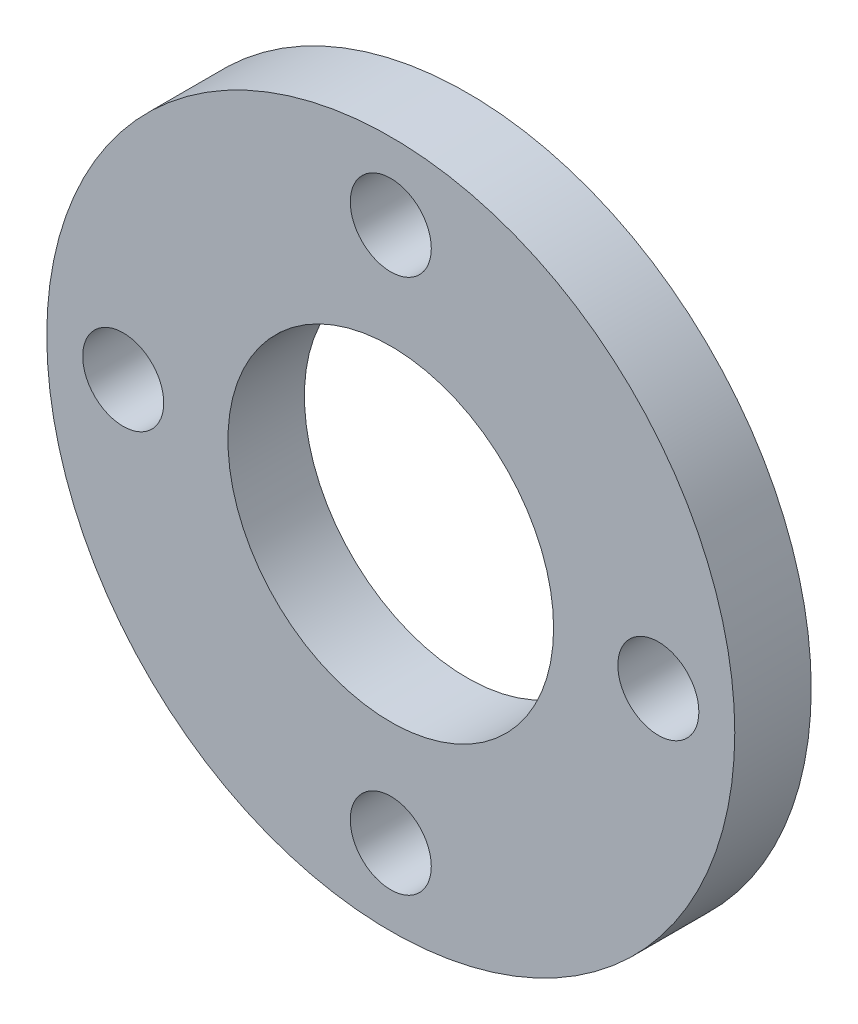
SolidWorks part; units mm, degrees
ref_plane "Płaszczyzna przednia" through (0, 0, 0) normal (0, 0, 1) x (1, 0, 0)
ref_plane "Płaszczyzna górna" through (0, 0, 0) normal (0, 1, 0) x (1, 0, 0)
ref_plane "Płaszczyzna prawa" through (0, 0, 0) normal (1, 0, 0) x (0, 0, -1)
sketch "Szkic1" plane through (0, 0, 0) normal (0, 0, 1) x (1, 0, 0)
  circle A0 centre (0, 0) radius 45
  circle A1 centre (0, 0) radius 35 construction
  circle A2 centre (0, 35) radius 5.3
  circle A3 centre (35, 0) radius 5.3
  circle A4 centre (0, -35) radius 5.3
  circle A5 centre (-35, 0) radius 5.3
  circle A6 centre (0, 0) radius 21.3
  dimension "D1" = 90
  dimension "D2" = 70
  dimension "D3" = 10.6
  dimension "D6" = 42.6
extrude "Dodanie-wyciągnięcie3" add sketch "Szkic1" along normal blind 10 contours A0 A5 A1 A2 A3 A4 | A5 A1 A4 A3 A2 A6
